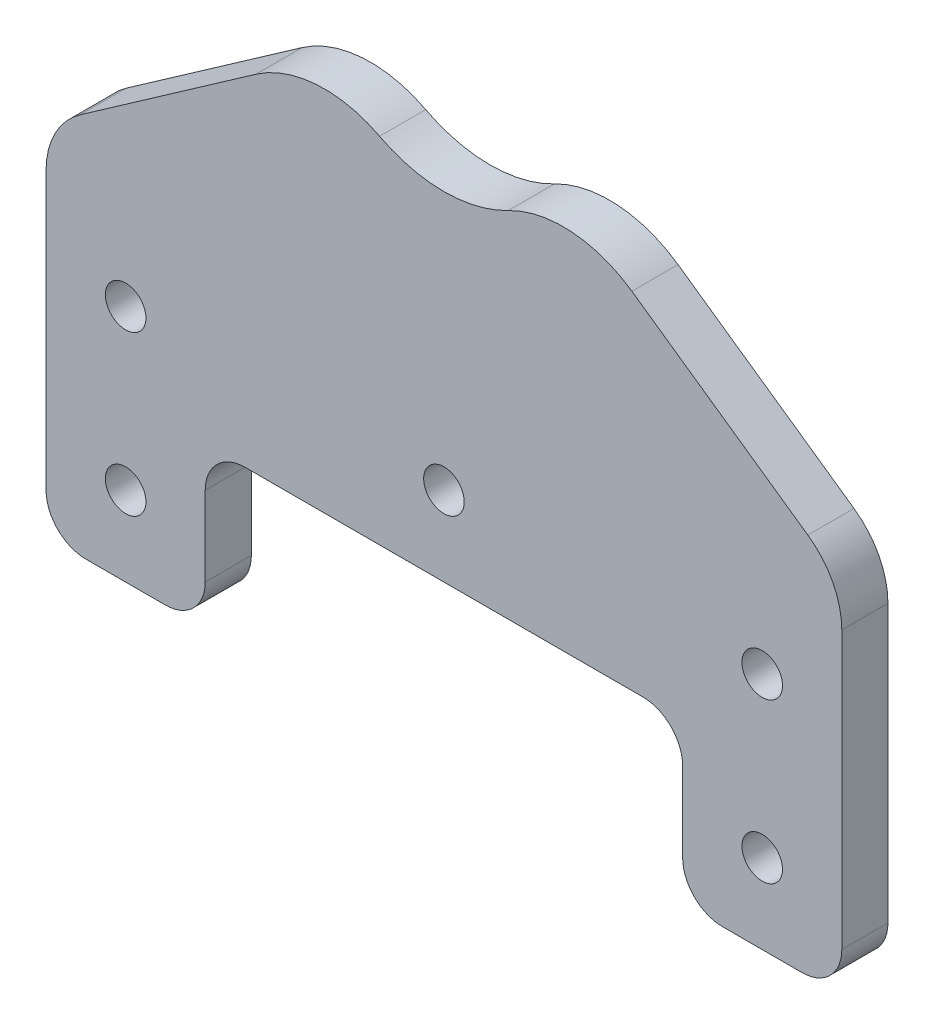
SolidWorks part; units mm, degrees
ref_plane "正面" through (0, 0, 0) normal (0, 0, 1) x (1, 0, 0)
ref_plane "平面" through (0, 0, 0) normal (0, 1, 0) x (1, 0, 0)
ref_plane "右側面" through (0, 0, 0) normal (1, 0, 0) x (0, 0, -1)
sketch "ｽｹｯﾁ1" plane through (0, 0, 0) normal (0, 0, 1) x (1, 0, 0)
  line L0 (-50, -60) -> (50, -60)
  line L1 (-50, -30) -> (-50, -60)
  line L2 (50, -30) -> (50, -60)
  line L3 (0, 0) -> (0, -30) construction
  line L4 (-40, -30) -> (-40, -50) construction
  line L5 (-40, -50) -> (40, -50) construction
  line L6 (40, -50) -> (40, -30) construction
  line L7 (-50, -30) -> (50, -30) construction
  circle A0 centre (0, 0) radius 7.5
  arc A2 (-50, -30) -> (50, -30) centre (0, -30) cw
  circle A3 centre (-40, -50) radius 2.55
  circle A4 centre (0, -50) radius 2.55
  circle A5 centre (40, -50) radius 2.55
  dimension "D1" = 100
  dimension "D2" = 15
  dimension "D3" = 30
  dimension "D4" = 30
  dimension "D8" = 5.1
  dimension "D5" = 10
  dimension "D6" = 10
  dimension "D7" = 10
extrude "ﾎﾞｽ - 押し出し1" add sketch "ｽｹｯﾁ1" along normal blind 5.8
sketch "ｽｹｯﾁ2" plane through (0, 0, 5.8) normal (0, 0, 1) x (1, 0, 0)
  line L0 (0, 0) -> (0, -89.872) construction
  line L1 (-50, -60) -> (-30, -60)
  line L2 (-50, -60) -> (-50, -80)
  line L3 (-50, -80) -> (-30, -80)
  line L4 (-30, -60) -> (-30, -80)
  line L5 (-40, -80) -> (-40, -60) construction
  line L6 (40, -80) -> (40, -60) construction
  line L7 (30, -60) -> (30, -80)
  line L8 (50, -80) -> (30, -80)
  line L9 (50, -60) -> (50, -80)
  line L10 (50, -60) -> (30, -60)
  circle A0 centre (-40, -70) radius 2.55
  circle A1 centre (-40, -50) radius 2.55 construction
  circle A2 centre (40, -70) radius 2.55
  dimension "D1" = 20
  dimension "D2" = 20
extrude "ﾎﾞｽ - 押し出し2" add sketch "ｽｹｯﾁ2" against normal up to surface (5.8 mm away) up to face at (-37.45, -50, 0)
fillet "ﾌｨﾚｯﾄ1" radius 5 6 edges at (-30, -60, 2.9) (30, -60, 2.9) (50, -80, 2.9) (30, -80, 2.9) (-30, -80, 2.9) (-50, -80, 2.9)
sketch "ｽｹｯﾁ3" plane through (0, 0, 0) normal (0, 0, -1) x (-1, 0, 0)
  line L0 (-45.7346, -32.0142) -> (-23.6196, -16.5337)
  line L1 (-50, -75) -> (-50, -30) construction
  line L2 (23.6196, -16.5337) -> (45.7346, -32.0142)
  line L3 (50, -30) -> (50, -75) construction
  line L4 (50, -35) -> (-50, -35) construction
  line L5 (-14.3366, -10.0356) -> (0, 0) construction
  line L6 (0, 0) -> (14.3366, -10.0356) construction
  line L12 (-50, -30) -> (-50, -75)
  line L13 (-45, -80) -> (-35, -80)
  line L14 (-30, -75) -> (-30, -65)
  line L15 (-25, -60) -> (25, -60)
  line L16 (30, -65) -> (30, -75)
  line L17 (35, -80) -> (45, -80)
  line L18 (50, -75) -> (50, -30)
  line L19 (-50, -40.2066) -> (-50, -75)
  line L20 (-45, -80) -> (-35, -80)
  line L21 (-30, -75) -> (-30, -65)
  line L22 (-25, -60) -> (25, -60)
  line L23 (30, -65) -> (30, -75)
  line L24 (35, -80) -> (45, -80)
  line L25 (50, -75) -> (50, -40.2066)
  circle A0 centre (0, -50) radius 2.55 construction
  arc A1 (-8.0864, -15.5196) -> (8.0864, -15.5196) centre (0, 0) ccw
  arc A2 (8.0864, -15.5196) -> (23.6196, -16.5337) centre (15.0177, -28.8222) cw
  arc A3 (-8.0864, -15.5196) -> (-23.6196, -16.5337) centre (-15.0177, -28.8222) ccw
  arc A4 (45.7346, -32.0142) -> (50, -40.2066) centre (40, -40.2066) cw
  arc A5 (-45.7346, -32.0142) -> (-50, -40.2066) centre (-40, -40.2066) ccw
  arc A7 (-50, -75) -> (-45, -80) centre (-45, -75) ccw
  arc A8 (-35, -80) -> (-30, -75) centre (-35, -75) ccw
  arc A9 (-25, -60) -> (-30, -65) centre (-25, -65) ccw
  arc A10 (30, -65) -> (25, -60) centre (25, -65) ccw
  arc A11 (30, -75) -> (35, -80) centre (35, -75) ccw
  arc A12 (45, -80) -> (50, -75) centre (45, -75) ccw
  arc A13 (50, -30) -> (-50, -30) centre (0, -30) ccw
  arc A14 (-50, -75) -> (-45, -80) centre (-45, -75) ccw
  arc A15 (-35, -80) -> (-30, -75) centre (-35, -75) ccw
  arc A16 (-25, -60) -> (-30, -65) centre (-25, -65) ccw
  arc A17 (30, -65) -> (25, -60) centre (25, -65) ccw
  arc A18 (30, -75) -> (35, -80) centre (35, -75) ccw
  arc A19 (45, -80) -> (50, -75) centre (45, -75) ccw
  dimension "D3" = 35
  dimension "D4" = 15
  dimension "D5" = 10
  dimension "D1" = 0
  dimension "D2" = 15
extrude "ｶｯﾄ - 押し出し1" cut sketch "ｽｹｯﾁ3" against normal through all flip side to cut
